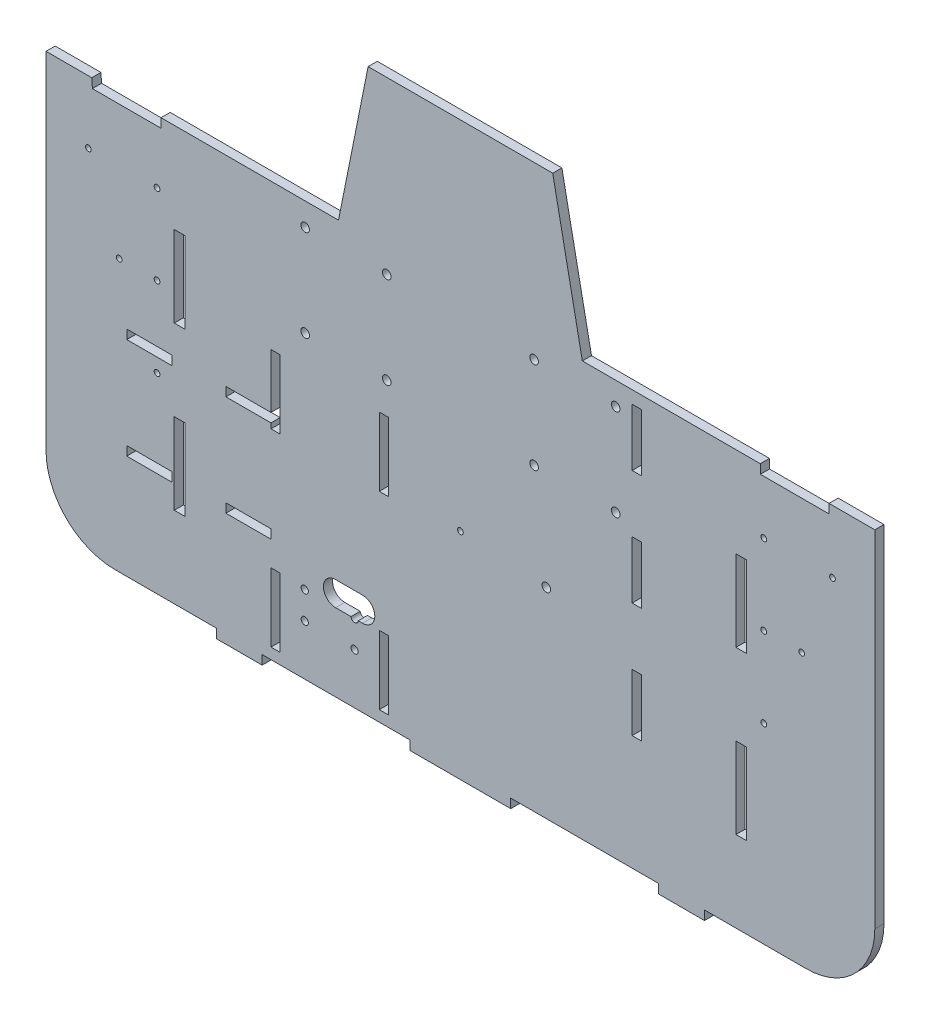
SolidWorks part; units mm, degrees
material "Gillfab4009"
ref_plane "Front Plane" through (0, 0, 0) normal (0, 0, 1) x (1, 0, 0)
ref_plane "Top Plane" through (0, 0, 0) normal (0, 1, 0) x (1, 0, 0)
ref_plane "Right Plane" through (0, 0, 0) normal (1, 0, 0) x (0, 0, -1)
sketch "Sketch2" plane through (0, 0, 0) normal (0, 0, 1) x (1, 0, 0)
  line L0 (-408.9218, 152.7574) -> (-459.7218, 152.7574)
  line L1 (332.7218, 152.7574) -> (135.2505, 152.7574)
  line L2 (-135.2505, 152.7574) -> (-332.1008, 152.7574)
  line L3 (-102.3945, 316.7286) -> (-135.2505, 152.7574)
  line L4 (102.3945, 316.7286) -> (-102.3945, 316.7286)
  line L6 (-459.7218, 152.7574) -> (-459.7218, -230.7826)
  line L7 (459.7218, 152.7574) -> (408.9218, 152.7574)
  line L8 (-303.52, -306.9826) -> (-383.5218, -306.9826)
  line L9 (-270.8, -317.1426) -> (-220, -317.1426)
  line L11 (408.9218, 142.6164) -> (408.9218, 152.7574)
  line L12 (332.7218, 142.6164) -> (408.9218, 142.6164)
  line L13 (332.7218, 152.7574) -> (332.7218, 142.6164)
  line L14 (-408.3008, 142.6164) -> (-332.1008, 142.6164)
  line L15 (-408.9218, 152.7574) -> (-408.3008, 142.6164)
  line L16 (-332.1008, 142.6164) -> (-332.1008, 152.7574)
  line L17 (305.6323, -37.2346) -> (317.4824, -37.2346)
  line L18 (305.6323, 52.6814) -> (305.6323, -37.2346)
  line L19 (317.4824, 52.6814) -> (305.6323, 52.6814)
  line L20 (317.4824, -37.2346) -> (317.4824, 52.6814)
  line L21 (305.6323, -217.0666) -> (317.4824, -217.0666)
  line L22 (317.4824, -217.0666) -> (317.4824, -127.1506)
  line L23 (317.4824, -127.1506) -> (305.6323, -127.1506)
  line L24 (305.6323, -127.1506) -> (305.6323, -217.0666)
  line L25 (252, -307.3966) -> (202.6964, -307.3966) construction
  line L27 (0, 316.7286) -> (0, 0) construction
  line L28 (0, 0) -> (0, -307.6709) construction
  line L39 (303.52, -306.9826) -> (383.5218, -306.9826)
  line L44 (-190.5, 75.1277) -> (-190.5, 11.4601) construction
  line L45 (-190.5, -52.225) -> (-190.5, -115.91) construction
  line L46 (-190.5, -179.5951) -> (-190.5, -243.2802) construction
  line L47 (190.5, 75.1277) -> (190.5, 14.3511) construction
  line L48 (190.5, -307.3966) -> (190.5, -243.6941) construction
  line L49 (190.5, 14.3511) -> (190.5, -115.91) construction
  line L52 (190.5, -115.91) -> (190.5, -243.6941) construction
  line L53 (459.7218, 152.7574) -> (459.7218, 465.1616) construction
  line L56 (459.7218, 152.7574) -> (459.7218, -230.7826)
  line L57 (-270.16, -79.447) -> (-210.16, -79.447)
  line L58 (-270.16, -79.447) -> (-270.16, -69.447)
  line L60 (-395.16, -79.447) -> (-210.16, -79.447)
  line L61 (-210.16, -79.447) -> (-210.16, -69.447)
  line L62 (102.3945, 316.7286) -> (135.2505, 152.7574)
  line L63 (-210.16, -69.447) -> (-395.16, -69.447)
  line L64 (-395.16, -69.447) -> (-395.16, -79.447)
  line L67 (-210.16, -69.447) -> (-270.16, -69.447)
  line L69 (-210.16, -191.2542) -> (-395.16, -191.2542) construction
  line L70 (0, -307.6709) -> (0, -629.2246) construction
  line L71 (-210.16, -181.2542) -> (-395.16, -181.2542) construction
  line L73 (-270.16, -191.2542) -> (-270.16, -181.2542) construction
  line L75 (202.6964, -243.6941) -> (190.5, -243.6941) construction
  line L76 (202.6964, -243.6941) -> (202.6964, -307.3966) construction
  line L79 (200.66, -179.5951) -> (190.5, -179.5951)
  line L80 (190.5, -179.5951) -> (190.5, -115.91)
  line L81 (200.66, -115.91) -> (190.5, -115.91)
  line L82 (200.66, -115.91) -> (200.66, -179.5951)
  line L83 (190.5, -52.225) -> (190.5, 11.4601)
  line L84 (200.66, 11.4601) -> (190.5, 11.4601)
  line L85 (200.66, 11.4601) -> (200.66, -52.225)
  line L86 (200.66, -52.225) -> (190.5, -52.225)
  line L87 (200.66, 138.8128) -> (190.5, 138.8128)
  line L88 (190.5, 75.1277) -> (190.5, 138.8128)
  line L89 (200.66, 75.1277) -> (190.5, 75.1277)
  line L90 (200.66, 138.8128) -> (200.66, 75.1277)
  line L103 (-210.16, -191.4142) -> (-210.16, -294.8827) construction
  line L105 (-210.16, -191.2542) -> (-210.16, -181.2542) construction
  line L106 (-210.16, -79.447) -> (-210.16, -181.2542) construction
  line L107 (-200, -191.4142) -> (-200, -294.8827) construction
  line L108 (-200, -294.8827) -> (-210.16, -294.8827) construction
  line L109 (-200, -218.6827) -> (-210.16, -218.6827) construction
  line L110 (-200, -85.1624) -> (-210.16, -85.1624) construction
  line L111 (-200, -85.1624) -> (-210.16, -85.1624)
  line L112 (-200, -218.6827) -> (-210.16, -218.6827)
  line L113 (-200, -294.8827) -> (-210.16, -294.8827)
  line L114 (-200, -218.6827) -> (-200, -294.8827)
  line L115 (-210.16, -79.447) -> (-210.16, -85.1624)
  line L116 (-210.16, -191.2542) -> (-210.16, -181.2542)
  line L117 (-210.16, -218.6827) -> (-210.16, -294.8827)
  line L118 (-270.16, -191.2542) -> (-270.16, -181.2542)
  line L120 (-210.16, -181.2542) -> (-270.16, -181.2542)
  line L121 (-210.16, -191.2542) -> (-270.16, -191.2542)
  line L125 (-210.16, -69.447) -> (-210.16, -8.9624)
  line L126 (-210.16, -8.9624) -> (-200, -8.9624)
  line L127 (-200, -8.9624) -> (-200, -85.1624)
  line L128 (305.6323, -37.2346) -> (305.6323, -217.0666) construction
  line L129 (317.4824, -37.2346) -> (317.4824, -217.0666) construction
  line L130 (-305.6323, -217.0666) -> (-317.4824, -217.0666)
  line L131 (-305.6323, -127.1506) -> (-305.6323, -217.0666)
  line L132 (-90, -218.6827) -> (-90, -294.8827)
  line L133 (-79.84, -218.6827) -> (-90, -218.6827)
  line L134 (-79.84, -294.8827) -> (-79.84, -218.6827)
  line L135 (-90, -294.8827) -> (-79.84, -294.8827)
  line L136 (-90, -218.6827) -> (-90, -294.8827)
  line L137 (-79.84, -218.6827) -> (-90, -218.6827)
  line L138 (-79.84, -294.8827) -> (-79.84, -218.6827)
  line L139 (-90, -294.8827) -> (-79.84, -294.8827)
  line L140 (-90, -8.9624) -> (-90, -85.1624)
  line L141 (-79.84, -8.9624) -> (-90, -8.9624)
  line L142 (-79.84, -85.1624) -> (-79.84, -8.9624)
  line L143 (-90, -85.1624) -> (-79.84, -85.1624)
  line L144 (-90, -8.9624) -> (-90, -85.1624)
  line L145 (-79.84, -8.9624) -> (-90, -8.9624)
  line L146 (-79.84, -85.1624) -> (-79.84, -8.9624)
  line L147 (-90, -85.1624) -> (-79.84, -85.1624)
  line L148 (-317.4824, -127.1506) -> (-305.6323, -127.1506)
  line L149 (-317.4824, -217.0666) -> (-317.4824, -127.1506)
  line L150 (-305.6323, -37.2346) -> (-317.4824, -37.2346)
  line L151 (-317.4824, -37.2346) -> (-317.4824, 52.6814)
  line L152 (-317.4824, 52.6814) -> (-305.6323, 52.6814)
  line L153 (-305.6323, 52.6814) -> (-305.6323, -37.2346)
  line L154 (-183, -317.1426) -> (-183, -226.646) construction
  line L155 (-183, -285.9366) -> (-107.07, -285.9366) construction
  line L156 (-108.5, -207.6709) -> (-138.5, -207.6709) construction
  line L157 (-108.5, -221.1709) -> (-138.5, -221.1709)
  line L158 (-108.5, -194.1709) -> (-138.5, -194.1709)
  line L159 (-90, -191.4142) -> (-90, -294.8827) construction
  line L160 (-145.035, -285.9366) -> (-145.035, -250.9366) construction
  line L161 (-172.69, -250.9366) -> (-117.38, -250.9366) construction
  line L162 (-145.035, -220.9366) -> (-145.035, -250.9366) construction
  line L163 (-172.69, -220.9366) -> (-117.38, -220.9366) construction
  line L164 (-210.16, -79.447) -> (-210.16, -69.447)
  line L166 (-55.8292, -306.9826) -> (-55.8292, -317.1426) construction
  line L167 (55.8292, -306.9826) -> (55.8292, -317.1426) construction
  line L168 (-55.8292, -306.9826) -> (-55.8292, -317.1426)
  line L169 (55.8292, -306.9826) -> (55.8292, -317.1426)
  line L170 (303.52, -306.9826) -> (252, -306.9826) construction
  line L171 (-303.52, -306.9826) -> (-252, -306.9826) construction
  line L174 (-303.52, -306.9826) -> (-270.8, -306.9826)
  line L175 (303.52, -306.9826) -> (270.8, -306.9826)
  line L178 (220, -317.1426) -> (270.8, -317.1426)
  line L179 (-270.8, -306.9826) -> (-270.8, -317.1426) construction
  line L180 (-270.8, -306.9826) -> (-270.8, -317.1426)
  line L181 (-220, -306.9826) -> (-220, -317.1426) construction
  line L182 (-220, -306.9826) -> (-220, -317.1426)
  line L183 (220, -306.9826) -> (220, -317.1426) construction
  line L184 (270.8, -306.9826) -> (270.8, -317.1426) construction
  line L185 (220, -306.9826) -> (220, -317.1426)
  line L186 (270.8, -306.9826) -> (270.8, -317.1426)
  line L187 (-55.8292, -317.1426) -> (55.8292, -317.1426) construction
  line L188 (-55.8292, -317.1426) -> (55.8292, -317.1426)
  line L189 (55.8292, -306.9826) -> (220, -306.9826)
  line L190 (-220, -306.9826) -> (-55.8292, -306.9826)
  line L195 (-210.16, -79.447) -> (-260.16, -79.447)
  line L196 (-210.16, -69.447) -> (-260.16, -69.447)
  line L197 (-260.16, -79.447) -> (-260.16, -69.447)
  line L198 (-320.16, -79.447) -> (-370.16, -79.447)
  line L199 (-320.16, -79.447) -> (-320.16, -69.287)
  line L200 (-370.16, -79.447) -> (-370.16, -69.287)
  line L201 (-320.16, -69.287) -> (-370.16, -69.287)
  line L202 (-210.16, -191.2542) -> (-260.16, -191.2542)
  line L203 (-210.16, -191.2542) -> (-210.16, -180.8741)
  line L206 (-210.16, -191.2542) -> (-210.16, -181.2542)
  line L207 (-210.16, -191.2542) -> (-260.16, -191.2542)
  line L208 (-210.16, -181.2542) -> (-260.16, -181.2542)
  line L209 (-260.16, -191.2542) -> (-260.16, -181.2542)
  line L210 (-320.16, -191.4142) -> (-320.16, -181.2542)
  line L211 (-320.16, -191.4142) -> (-370.16, -191.4142)
  line L212 (-320.16, -181.2542) -> (-370.16, -181.2542)
  line L213 (-370.16, -191.4142) -> (-370.16, -181.2542)
  arc A0 (-383.5218, -306.9826) -> (-459.7218, -230.7826) centre (-383.5218, -230.7826) cw
  arc A2 (383.5218, -306.9826) -> (459.7218, -230.7826) centre (383.5218, -230.7826) ccw
  circle A6 centre (336.5503, -94.6874) radius 3.175
  circle A7 centre (378.5738, -5.7874) radius 3.175
  circle A8 centre (336.5503, -5.7874) radius 3.175
  circle A9 centre (336.5503, 83.1126) radius 3.175
  circle A10 centre (412.7503, 83.1126) radius 3.175
  circle A11 centre (-412.7503, 83.1126) radius 3.175
  circle A12 centre (-336.5503, 83.1126) radius 3.175
  circle A13 centre (-336.5503, -5.7874) radius 3.175
  circle A14 centre (-378.5738, -5.7874) radius 3.175
  circle A15 centre (-336.5503, -94.6874) radius 3.175
  circle A18 centre (172.2755, 127.3574) radius 4.7625
  circle A19 centre (172.2755, 25.7574) radius 4.7625
  circle A20 centre (81.7245, 25.7574) radius 4.7625
  circle A21 centre (81.7245, 127.3574) radius 4.7625
  circle A22 centre (-81.7245, 25.7574) radius 4.7625
  circle A23 centre (-81.7245, 127.3574) radius 4.7625
  circle A24 centre (-172.2755, 127.3574) radius 4.7625
  circle A25 centre (-172.2755, 25.7574) radius 4.7625
  circle A26 centre (0, -78.3826) radius 3.175
  circle A28 centre (95.25, -84.7326) radius 4.7625
  arc A29 (-108.5, -221.1709) -> (-108.5, -194.1709) centre (-108.5, -207.6709) ccw
  arc A30 (-138.5, -194.1709) -> (-138.5, -221.1709) centre (-138.5, -207.6709) ccw
  circle A31 centre (-172.69, -220.9366) radius 4
  circle A32 centre (-117.38, -220.9366) radius 4
  circle A33 centre (-117.38, -250.9366) radius 4
  circle A34 centre (-172.69, -250.9366) radius 4
  point P33 (0, 0)
  point P59 (-123.5, -207.6709)
  point P74 (-145.035, -250.9366)
  point P128 (-95, -207.6709)
  point P173 (-145.035, -220.9366)
  point P198 (0, 0)
  dimension "D1" = 76.2
  dimension "D8" = 76.2
  dimension "D21" = 27
  dimension "D22" = 30
  dimension "D33" = 8
  dimension "D34" = 50
  dimension "D3" = 919.4436
  dimension "D4" = 305.6323
  dimension "D5" = 183
  dimension "D6" = 31.206
  dimension "D7" = 152.7574
  dimension "D9" = 75.93
  dimension "D10" = 50
  dimension "D11" = 35
  dimension "D12" = 10.16
  dimension "D13" = 190.5
  dimension "D14" = 190.5
  dimension "D15" = 50.8
  dimension "D16" = 0
  dimension "D17" = 50.8
  dimension "D18" = 76.2
  dimension "D19" = 0
  dimension "D23" = 5
  dimension "D24" = 55.31
  dimension "D25" = 11.8501
  dimension "D26" = 52.6814
  dimension "D27" = 89.916
  dimension "D28" = 89.916
  dimension "D29" = 89.916
  dimension "D30" = 316.7286
  dimension "D31" = 55.31
  dimension "D32" = 30
  dimension "D35" = 60
  dimension "D36" = 10.16
  dimension "D37" = 50
  dimension "D38" = 50
  dimension "D39" = 10.16
  dimension "D20" = 0
extrude "Boss-Extrude1" add sketch "Sketch2" against normal blind 10.16 contours L39 A2 L56 L7 L11 L12 L13 L1 L62 L4 L3 L2 L16 L14 L15 L0 L6 A0 L8 L174 L180 L9 L182 L190 L168 L188 L169 L189 L185 L178 L186 L175 A34 A33 A32 A31 A30 L158 A29 L157 A28 A26 A25 | L121 L209 L120 L118 | L57 L197 L67 L58
sketch "Sketch3" plane through (0, 0, 0) normal (0, 0, 1) x (1, 0, 0)
  line L0 (250, -275.561) -> (419.7218, -275.561) construction
  line L1 (419.7218, -275.561) -> (419.7218, 24.439) construction
  line L2 (419.7218, 24.439) -> (250, 24.439) construction
  line L3 (459.7218, -230.7826) -> (459.7218, 152.7574) construction
  line L4 (-545.9218, 194.0186) -> (545.9218, 194.0186) construction
  line L5 (-545.9218, 213.0186) -> (545.9218, 213.0186) construction
  dimension "D1" = 40
  dimension "D2" = 19
sketch "Sketch4" plane through (0, 152.7574, 0) normal (0, 1, 0) x (1, 0, 0)
  line L0 (-102.3945, 0) -> (-135.2505, 0) construction
  line L1 (-459.7218, 10.16) -> (-108.0462, 10.16)
  line L2 (-459.7218, 10.16) -> (-459.7218, 0)
  line L3 (-459.7218, 0) -> (-108.0462, 0)
  line L4 (-108.0462, 10.16) -> (-108.0462, 0)
